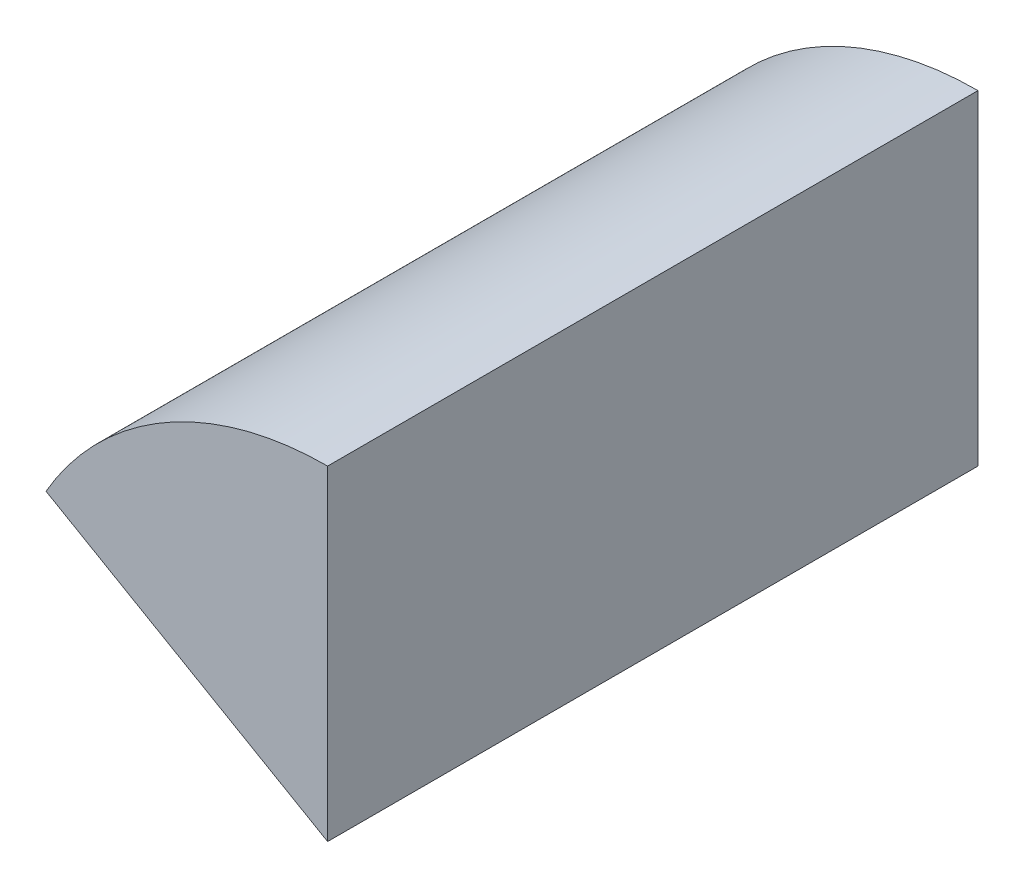
SolidWorks part; units mm, degrees
ref_plane "Alzado" through (0, 0, 0) normal (0, 0, 1) x (1, 0, 0)
ref_plane "Planta" through (0, 0, 0) normal (0, 1, 0) x (1, 0, 0)
ref_plane "Vista lateral" through (0, 0, 0) normal (1, 0, 0) x (0, 0, -1)
sketch "Croquis1" plane through (0, 0, 0) normal (0, 0, 1) x (1, 0, 0)
  line L0 (0, 25) -> (0, 0)
  line L2 (-21.6506, 12.5) -> (0, 0)
  arc A0 (0, 25) -> (-21.6506, 12.5) centre (0, 0) ccw
  dimension "D1" = 50
  dimension "D2" = 60
extrude "Saliente-Extruir1" add sketch "Croquis1" along normal blind 50
sketch "Croquis2" plane through (0, 0, 0) normal (0, 0, -1) x (-1, 0, 0)
  circle A0 centre (7.7821, 14.0406) radius 5
  dimension "D1" = 10
extrude "Cortar-Extruir1" cut sketch "Croquis2" against normal blind 10
